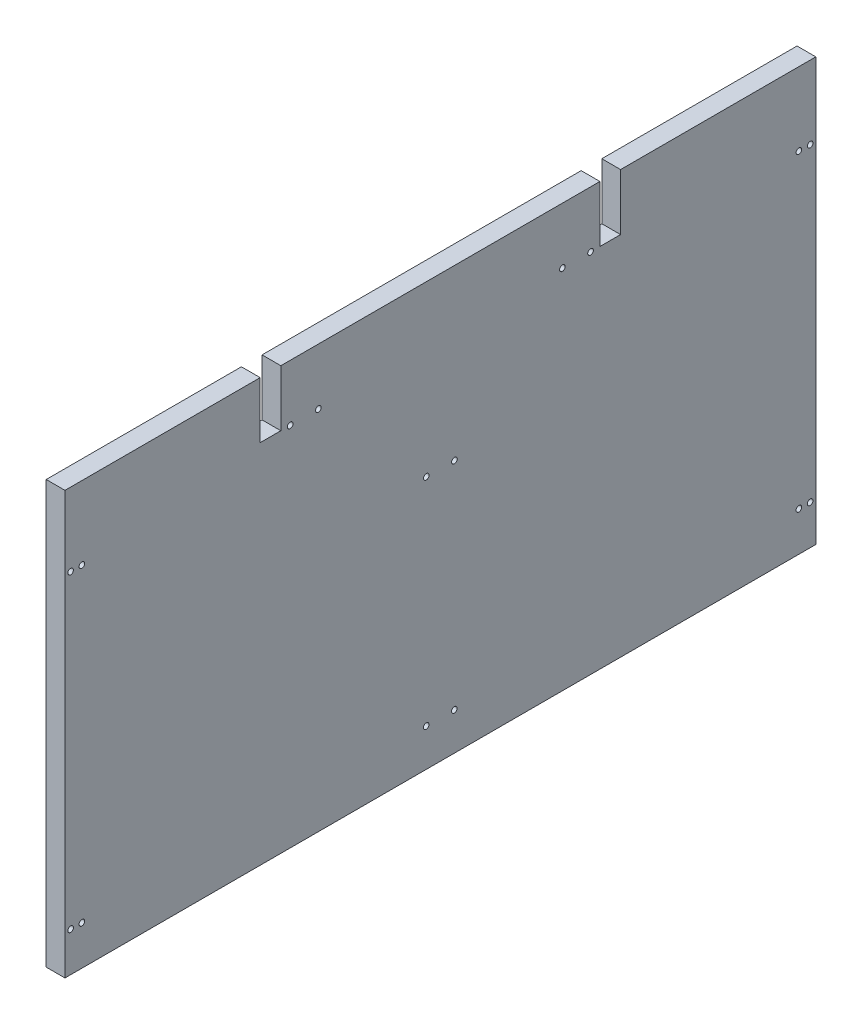
SolidWorks part; units mm, degrees
ref_plane "前视基准面" through (0, 0, 0) normal (0, 0, 1) x (1, 0, 0)
ref_plane "上视基准面" through (0, 0, 0) normal (0, 1, 0) x (1, 0, 0)
ref_plane "右视基准面" through (0, 0, 0) normal (1, 0, 0) x (0, 0, -1)
sketch "草图1" plane through (0, 0, 0) normal (1, 0, 0) x (0, 0, -1)
  line L0 (-85, 112.5) -> (85, 112.5)
  line L1 (-200, 112.5) -> (-96, 112.5)
  line L2 (-200, 112.5) -> (-200, -112.5)
  line L3 (-200, -112.5) -> (200, -112.5)
  line L4 (200, 112.5) -> (200, -112.5)
  line L5 (-200, 112.5) -> (200, -112.5) construction
  line L6 (-200, -112.5) -> (200, 112.5) construction
  line L7 (85, 112.5) -> (85, 82.5)
  line L8 (85, 82.5) -> (96, 82.5)
  line L9 (96, 82.5) -> (96, 112.5)
  line L10 (-85, 112.5) -> (-85, 82.5)
  line L11 (-85, 82.5) -> (-96, 82.5)
  line L12 (-96, 82.5) -> (-96, 112.5)
  line L13 (-85, 112.5) -> (85, 112.5)
  line L14 (96, 112.5) -> (200, 112.5)
  point P0 (0, 0)
  point P9 (0, 112.5)
  dimension "D1" = 400
  dimension "D2" = 225
extrude "凸台-拉伸1" add sketch "草图1" along normal blind 10 contours L14 L9 L8 L7 L0 L10 L11 L12 L1 L2 L3 L4
sketch "草图2" plane through (0, 0, 0) normal (-1, 0, 0) x (0, 0, 1)
  line L0 (-84, -105.5) -> (-66, -105.5) construction
  line L1 (200, -112.5) -> (-200, -112.5) construction
  line L2 (-66, -105.5) -> (-9, -105.5) construction
  line L3 (-9, -105.5) -> (9, -105.5) construction
  line L4 (9, -105.5) -> (66, -105.5) construction
  line L5 (66, -105.5) -> (84, -105.5) construction
  line L6 (200, 112.5) -> (200, -112.5) construction
  circle A0 centre (-84, -105.5) radius 1.5
  circle A2 centre (-66, -105.5) radius 1.5
  circle A3 centre (-9, -105.5) radius 1.5
  circle A4 centre (9, -105.5) radius 1.5
  circle A5 centre (66, -105.5) radius 1.5
  circle A6 centre (84, -105.5) radius 1.5
  dimension "D1" = 3
  dimension "D2" = 3
  dimension "D3" = 3
  dimension "D4" = 3
  dimension "D5" = 3
  dimension "D6" = 7
  dimension "D7" = 3
  dimension "D8" = 116
  dimension "D9" = 18
  dimension "D10" = 18
  dimension "D11" = 18
  dimension "D13" = 57
  dimension "D14" = 57
extrude "切除-拉伸1" cut sketch "草图2" against normal blind 6
sketch "草图3" plane through (10, 0, 0) normal (1, 0, 0) x (0, 0, -1)
  line L0 (191, -91.5) -> (197, -91.5) construction
  line L1 (-200, -112.5) -> (200, -112.5) construction
  line L2 (200, 112.5) -> (200, -112.5) construction
  line L3 (191, 73.5) -> (197, 73.5) construction
  line L4 (96, 112.5) -> (200, 112.5) construction
  circle A0 centre (197, -91.5) radius 1.5
  circle A2 centre (191, -91.5) radius 1.5
  circle A3 centre (191, 73.5) radius 1.5
  circle A4 centre (197, 73.5) radius 1.5
  dimension "D1" = 3
  dimension "D2" = 3
  dimension "D6" = 3
  dimension "D7" = 3
  dimension "D3" = 21
  dimension "D4" = 3
  dimension "D5" = 6
  dimension "D8" = 39
extrude "切除-拉伸2" cut sketch "草图3" against normal blind 5
mirror "镜向1" about plane through (0, 0, 0) normal (0, 0, 1) of "切除-拉伸2"
sketch "草图4" plane through (10, 0, 0) normal (1, 0, 0) x (0, 0, -1)
  line L0 (-7.57, -92.5) -> (7.43, -92.5) construction
  line L1 (200, 112.5) -> (200, -112.5) construction
  line L2 (-200, -112.5) -> (200, -112.5) construction
  circle A0 centre (7.43, -92.5) radius 1.5
  circle A1 centre (-7.57, -92.5) radius 1.5
  dimension "D1" = 3
  dimension "D2" = 3
  dimension "D3" = 15
  dimension "D4" = 192.57
  dimension "D5" = 20
extrude "切除-拉伸3" cut sketch "草图4" against normal blind 10
sketch "草图5" plane through (10, 0, 0) normal (1, 0, 0) x (0, 0, -1)
  line L0 (-80, 82.5) -> (-65, 82.5) construction
  line L3 (-200, -112.5) -> (200, -112.5) construction
  line L4 (-200, 112.5) -> (-200, -112.5) construction
  circle A0 centre (-80, 82.5) radius 1.5
  circle A1 centre (-65, 82.5) radius 1.5
  dimension "D1" = 3
  dimension "D2" = 3
  dimension "D3" = 15
  dimension "D4" = 195
  dimension "D5" = 120
extrude "切除-拉伸4" cut sketch "草图5" against normal blind 10
mirror "镜向2" about plane through (0, 0, 0) normal (0, 0, 1) of "切除-拉伸4"
sketch "草图6" plane through (10, 0, 0) normal (1, 0, 0) x (0, 0, -1)
  line L0 (-7.5, 22.5) -> (7.5, 22.5) construction
  line L1 (-7.57, -92.5) -> (7.43, -92.5) construction
  line L2 (-200, 112.5) -> (-200, -112.5) construction
  circle A0 centre (-7.5, 22.5) radius 1.5
  circle A1 centre (7.5, 22.5) radius 1.5
  dimension "D1" = 3
  dimension "D2" = 3
  dimension "D3" = 15
  dimension "D4" = 115
  dimension "D5" = 192.5
extrude "切除-拉伸5" cut sketch "草图6" against normal blind 10
